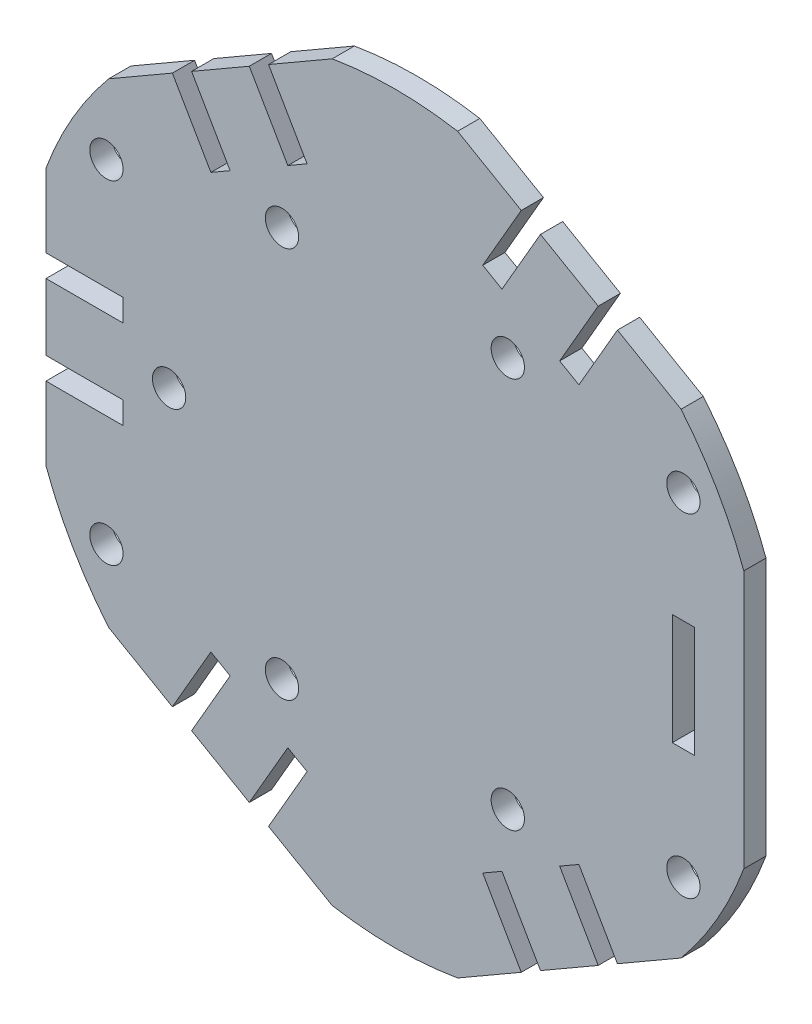
SolidWorks part; units mm, degrees
material "Acrylic (Medium-high impact)"
ref_plane "Front Plane" through (0, 0, 0) normal (0, 0, 1) x (1, 0, 0)
ref_plane "Top Plane" through (0, 0, 0) normal (0, 1, 0) x (1, 0, 0)
ref_plane "Right Plane" through (0, 0, 0) normal (1, 0, 0) x (0, 0, -1)
sketch "Model" plane through (0, 0, 0) normal (0, 0, 1) x (1, 0, 0)
  line L133 (2079.5132, 1320.3247) -> (2079.5132, 1322.3247)
  line L134 (2079.5132, 1328.3247) -> (2079.5132, 1330.3247)
  line L135 (2079.5132, 1330.3247) -> (2072.5738, 1330.3247)
  line L136 (2072.5738, 1328.3247) -> (2079.5132, 1328.3247)
  line L137 (2079.5132, 1320.3247) -> (2072.5738, 1320.3247)
  line L138 (2072.5738, 1322.3247) -> (2079.5132, 1322.3247)
  line L139 (2072.5738, 1328.3247) -> (2072.5738, 1322.3247)
  line L140 (2072.5738, 1336.9434) -> (2072.5738, 1330.3247)
  line L142 (2072.5738, 1320.3247) -> (2072.5738, 1313.706)
  line L143 (2087.4237, 1344.0261) -> (2089.1557, 1345.0261)
  line L144 (2094.3519, 1348.0261) -> (2096.0839, 1349.0261)
  line L145 (2096.0839, 1349.0261) -> (2092.6143, 1355.0357)
  line L146 (2090.8822, 1354.0357) -> (2094.3519, 1348.0261)
  line L147 (2087.4237, 1344.0261) -> (2083.954, 1350.0357)
  line L148 (2085.6861, 1351.0357) -> (2089.1557, 1345.0261)
  line L149 (2090.8822, 1354.0357) -> (2085.6861, 1351.0357)
  line L150 (2098.3463, 1358.3451) -> (2092.6143, 1355.0357)
  line L152 (2083.954, 1350.0357) -> (2078.222, 1346.7264)
  line L153 (2096.0839, 1301.6233) -> (2094.3519, 1302.6233)
  line L154 (2089.1557, 1305.6233) -> (2087.4237, 1306.6233)
  line L155 (2087.4237, 1306.6233) -> (2083.954, 1300.6136)
  line L156 (2085.6861, 1299.6136) -> (2089.1557, 1305.6233)
  line L157 (2096.0839, 1301.6233) -> (2092.6143, 1295.6136)
  line L158 (2090.8822, 1296.6136) -> (2094.3519, 1302.6233)
  line L159 (2085.6861, 1299.6136) -> (2090.8822, 1296.6136)
  line L160 (2078.222, 1303.923) -> (2083.954, 1300.6136)
  line L162 (2092.6143, 1295.6136) -> (2098.3463, 1292.3043)
  line L163 (2120.5652, 1306.6233) -> (2118.8332, 1305.6233)
  line L164 (2113.637, 1302.6233) -> (2111.905, 1301.6233)
  line L165 (2111.905, 1301.6233) -> (2115.3746, 1295.6136)
  line L166 (2117.1067, 1296.6136) -> (2113.637, 1302.6233)
  line L167 (2120.5652, 1306.6233) -> (2124.0349, 1300.6136)
  line L168 (2122.3028, 1299.6136) -> (2118.8332, 1305.6233)
  line L169 (2117.1067, 1296.6136) -> (2122.3028, 1299.6136)
  line L170 (2109.6427, 1292.3043) -> (2115.3746, 1295.6136)
  line L172 (2124.0349, 1300.6136) -> (2129.7669, 1303.923)
  line L173 (2111.905, 1349.0261) -> (2113.637, 1348.0261)
  line L174 (2118.8332, 1345.0261) -> (2120.5652, 1344.0261)
  line L175 (2120.5652, 1344.0261) -> (2124.0349, 1350.0357)
  line L176 (2122.3028, 1351.0357) -> (2118.8332, 1345.0261)
  line L177 (2111.905, 1349.0261) -> (2115.3746, 1355.0357)
  line L178 (2117.1067, 1354.0357) -> (2113.637, 1348.0261)
  line L179 (2122.3028, 1351.0357) -> (2117.1067, 1354.0357)
  line L180 (2129.7669, 1346.7264) -> (2124.0349, 1350.0357)
  line L182 (2115.3746, 1355.0357) -> (2109.6427, 1358.3451)
  line L183 (2135.4151, 1336.9434) -> (2135.4151, 1313.706)
  line L184 (2130.9769, 1330.3247) -> (2130.9769, 1320.3247)
  line L185 (2128.9769, 1320.3247) -> (2128.9769, 1330.3247)
  line L186 (2128.9769, 1320.3247) -> (2130.9769, 1320.3247)
  line L560 (2128.9769, 1330.3247) -> (2130.9769, 1330.3247)
  circle A65 centre (2083.6596, 1325.3247) radius 1.5
  circle A66 centre (2093.827, 1342.9352) radius 1.5
  circle A67 centre (2093.827, 1307.7142) radius 1.5
  circle A68 centre (2114.1619, 1307.7142) radius 1.5
  circle A69 centre (2114.1619, 1342.9352) radius 1.5
  arc A70 (2129.7669, 1303.923) -> (2135.4151, 1313.706) centre (2103.9945, 1325.3247) ccw
  arc A71 (2098.3463, 1292.3043) -> (2109.6427, 1292.3043) centre (2103.9945, 1325.3247) ccw
  arc A72 (2072.5738, 1313.706) -> (2078.222, 1303.923) centre (2103.9945, 1325.3247) ccw
  arc A73 (2078.222, 1346.7264) -> (2072.5738, 1336.9434) centre (2103.9945, 1325.3247) ccw
  arc A74 (2109.6427, 1358.3451) -> (2098.3463, 1358.3451) centre (2103.9945, 1325.3247) ccw
  arc A75 (2135.4151, 1336.9434) -> (2129.7669, 1346.7264) centre (2103.9945, 1325.3247) ccw
  circle A76 centre (2078.0137, 1340.3247) radius 1.5
  circle A77 centre (2078.0137, 1310.3247) radius 1.5
  circle A78 centre (2129.9752, 1340.3247) radius 1.5
  circle A79 centre (2129.9752, 1310.3247) radius 1.5
extrude "Boss-Extrude2" add sketch "Model" along normal blind 2
